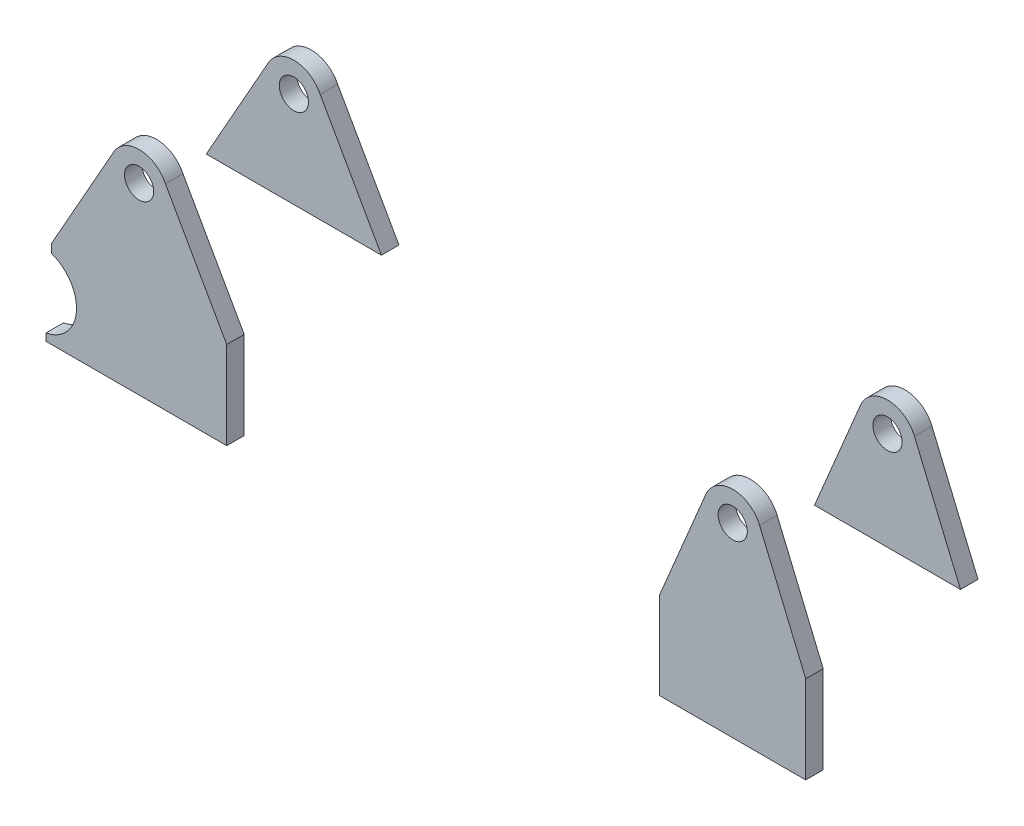
SolidWorks part; units mm, degrees
ref_plane "Front Plane" through (0, 0, 0) normal (0, 0, 1) x (1, 0, 0)
ref_plane "Top Plane" through (0, 0, 0) normal (0, 1, 0) x (1, 0, 0)
ref_plane "Right Plane" through (0, 0, 0) normal (1, 0, 0) x (0, 0, -1)
sketch "Sketch1" plane through (0, 0, 0) normal (0, 0, 1) x (1, 0, 0)
  line L0 (-745.1446, -553.3409) -> (-146.7576, -553.3409) construction
  line L1 (-745.1446, -553.3409) -> (-146.7576, -553.3409)
  line L2 (-737.4286, -553.3409) -> (-716.1399, -515.5758)
  line L3 (-698.3946, -516.1984) -> (-677.4286, -553.3409)
  line L4 (-711.9899, -518.4382) -> (-702.8674, -522.5346) construction
  line L5 (-500.2511, -516.4563) -> (-508.0021, -522.7748) construction
  line L6 (-707.4286, -520.4864) -> (-707.4286, -553.3409) construction
  line L7 (-513.3474, -515.7455) -> (-529.1266, -553.3409)
  line L9 (-494.9058, -515.7455) -> (-479.1266, -553.3409)
  line L11 (-745.1446, -583.3409) -> (-146.7581, -583.3409) construction
  line L12 (-739.3147, -583.3409) -> (-146.7581, -583.3409)
  line L16 (-677.4286, -553.3409) -> (-677.4286, -583.3409)
  line L17 (-737.4286, -553.3409) -> (-737.4286, -556.3319)
  line L19 (-504.1266, -519.6156) -> (-504.1266, -553.3409) construction
  line L20 (-529.1266, -553.3409) -> (-529.1266, -583.3409)
  line L21 (-529.1266, -583.3409) -> (-479.1266, -583.3409)
  line L22 (-479.1266, -583.3409) -> (-479.1266, -553.3409)
  line L23 (-739.3147, -580.8409) -> (-739.3147, -583.3409)
  circle A0 centre (-707.4286, -520.4864) radius 10
  circle A2 centre (-504.1266, -519.6156) radius 10
  arc A3 (-728.8602, -568.341) -> (-754.2602, -568.341) centre (-741.5602, -568.341) ccw
  arc A4 (-728.8602, -568.341) -> (-737.4286, -556.3319) centre (-741.5602, -568.341) ccw
  arc A5 (-754.2602, -568.341) -> (-728.8602, -568.341) centre (-741.5602, -568.341) ccw
  arc A6 (-739.3147, -580.8409) -> (-728.8602, -568.341) centre (-741.5602, -568.341) ccw
  spline S1 degree 3 poles (-702.4287, -520.5174) (-702.3667, -510.5176) (-712.3665, -510.4556) (-712.4285, -520.4554) (-712.4906, -530.4552) (-702.4908, -530.5172) (-702.4287, -520.5174) (-702.3667, -510.5176) (-712.3665, -510.4556) knots -0.5 0 0 0 0.5 0.5 0.5 1 1 1 1.5 1.5 1.5 weights 1 0.333333 0.333333 1 0.333333 0.333333 1 0.333333 0.333333 only from (-702.4287, -520.5174) to (-702.4287, -520.5174) construction
  spline S2 degree 3 poles (-499.1267, -519.6466) (-499.0647, -509.6468) (-509.0645, -509.5847) (-509.1265, -519.5845) (-509.1886, -529.5843) (-499.1887, -529.6464) (-499.1267, -519.6466) (-499.0647, -509.6468) (-509.0645, -509.5847) knots -0.5 0 0 0 0.5 0.5 0.5 1 1 1 1.5 1.5 1.5 weights 1 0.333333 0.333333 1 0.333333 0.333333 1 0.333333 0.333333 only from (-499.1267, -519.6466) to (-499.1267, -519.6466) construction
  spline S3 degree 3 poles (-702.4287, -520.5174) (-702.3667, -510.5176) (-712.3665, -510.4556) (-712.4285, -520.4554) (-712.4906, -530.4552) (-702.4908, -530.5172) (-702.4287, -520.5174) (-702.3667, -510.5176) (-712.3665, -510.4556) knots -0.5 0 0 0 0.5 0.5 0.5 1 1 1 1.5 1.5 1.5 weights 1 0.333333 0.333333 1 0.333333 0.333333 1 0.333333 0.333333 only from (-702.4287, -520.5174) to (-702.4287, -520.5174)
  spline S4 degree 3 poles (-499.1267, -519.6466) (-499.0647, -509.6468) (-509.0645, -509.5847) (-509.1265, -519.5845) (-509.1886, -529.5843) (-499.1887, -529.6464) (-499.1267, -519.6466) (-499.0647, -509.6468) (-509.0645, -509.5847) knots -0.5 0 0 0 0.5 0.5 0.5 1 1 1 1.5 1.5 1.5 weights 1 0.333333 0.333333 1 0.333333 0.333333 1 0.333333 0.333333 only from (-499.1267, -519.6466) to (-499.1267, -519.6466)
  point P4 (-707.4286, -520.4864)
  point P13 (-707.4286, -520.4864)
  point P16 (-504.1266, -519.6156)
  dimension "D1" = 20
  dimension "D2" = 30
  dimension "D4" = 20
  dimension "D3" = 30
  dimension "D5" = 25
  dimension "D6" = 25
extrude "Boss-Extrude1" add sketch "Sketch1" along normal blind 6
ref_plane "Plane1" through (0, 0, -47) normal (0, 0, -1) x (-1, 0, 0)
sketch "Sketch2" plane through (0, 0, -47) normal (0, 0, -1) x (-1, 0, 0)
  line L0 (745.1446, -553.3409) -> (146.7581, -553.3409) construction
  line L1 (745.1446, -553.3409) -> (146.7581, -553.3409)
  line L6 (737.4286, -556.3319) -> (737.4286, -553.3409)
  line L7 (737.4286, -553.3409) -> (716.1399, -515.5758)
  line L8 (698.3946, -516.1984) -> (677.4286, -553.3409)
  line L9 (677.4286, -553.3409) -> (677.4286, -583.3409)
  line L10 (677.4286, -583.3409) -> (739.3147, -583.3409)
  line L11 (739.3147, -583.3409) -> (739.3147, -580.8409)
  line L12 (737.4286, -556.3319) -> (737.4286, -553.3409)
  line L13 (737.4286, -553.3409) -> (716.1399, -515.5758)
  line L14 (698.3946, -516.1984) -> (677.4286, -553.3409)
  line L15 (677.4286, -553.3409) -> (677.4286, -583.3409)
  line L16 (677.4286, -583.3409) -> (739.3147, -583.3409)
  line L17 (739.3147, -583.3409) -> (739.3147, -580.8409)
  line L19 (479.1266, -583.3409) -> (529.1266, -583.3409)
  line L20 (529.1266, -583.3409) -> (529.1266, -553.3409)
  line L21 (529.1266, -553.3409) -> (513.3474, -515.7455)
  line L22 (494.9058, -515.7455) -> (479.1266, -553.3409)
  line L23 (479.1266, -553.3409) -> (479.1266, -583.3409)
  line L24 (479.1266, -583.3409) -> (529.1266, -583.3409)
  line L25 (529.1266, -583.3409) -> (529.1266, -553.3409)
  line L26 (529.1266, -553.3409) -> (513.3474, -515.7455)
  line L27 (494.9058, -515.7455) -> (479.1266, -553.3409)
  line L28 (479.1266, -553.3409) -> (479.1266, -583.3409)
  circle A0 centre (504.1266, -519.6156) radius 5 construction
  arc A1 (513.3474, -515.7455) -> (494.9058, -515.7455) centre (504.1266, -519.6156) ccw
  arc A2 (737.4286, -556.3319) -> (739.3147, -580.8409) centre (741.5602, -568.341) ccw
  arc A3 (716.1399, -515.5758) -> (698.3946, -516.1984) centre (707.4286, -520.4864) ccw
  arc A4 (737.4286, -556.3319) -> (739.3147, -580.8409) centre (741.5602, -568.341) ccw
  arc A5 (716.1399, -515.5758) -> (698.3946, -516.1984) centre (707.4286, -520.4864) ccw
  arc A6 (513.3474, -515.7455) -> (494.9058, -515.7455) centre (504.1266, -519.6156) ccw
  circle A7 centre (707.4286, -520.4864) radius 5 construction
  circle A8 centre (504.1266, -519.6156) radius 5
  circle A9 centre (707.4286, -520.4864) radius 5
  dimension "D1" = 0
  dimension "D2" = 0
extrude "Boss-Extrude2" add sketch "Sketch2" along normal blind 6 separate body contours L13 A5 L14 L1 A9 | L26 A6 L27 L1 A8
